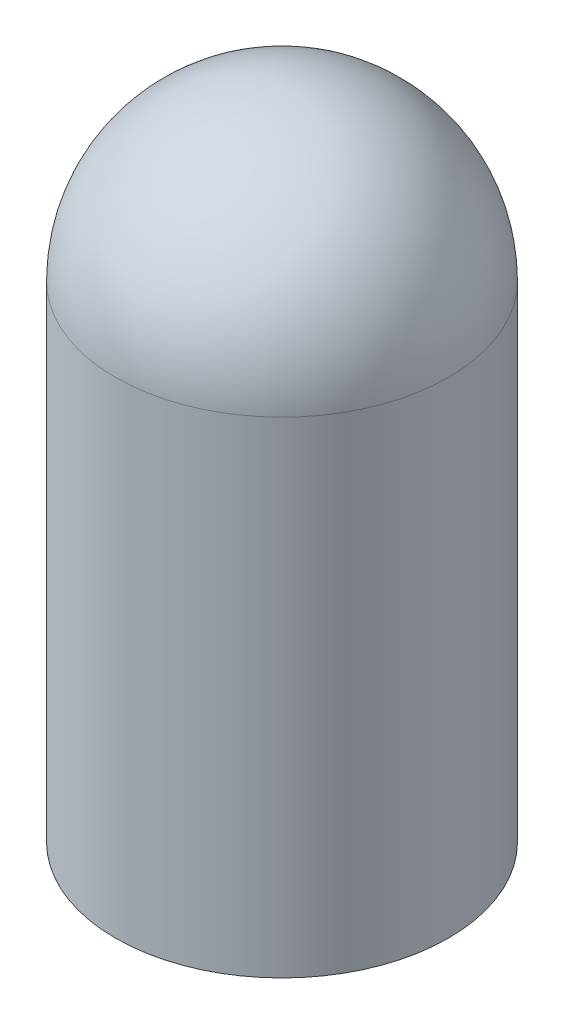
SolidWorks part; units mm, degrees
ref_plane "Front Plane" through (0, 0, 0) normal (0, 0, 1) x (1, 0, 0)
ref_plane "Top Plane" through (0, 0, 0) normal (0, 1, 0) x (1, 0, 0)
ref_plane "Right Plane" through (0, 0, 0) normal (1, 0, 0) x (0, 0, -1)
sketch "Sketch1" plane through (0, 0, 0) normal (0, 0, 1) x (1, 0, 0)
  line L0 (12, 0) -> (12, -35)
  line L1 (10.5, 0) -> (10.5, -35)
  line L2 (10.5, -35) -> (12, -35)
  line L3 (0, 12) -> (0, 10.5)
  line L4 (0, 12) -> (0, -44.4762) construction
  arc A0 (12, 0) -> (0, 12) centre (0, 0) ccw
  arc A1 (10.5, 0) -> (0, 10.5) centre (0, 0) ccw
  dimension "D1" = 21
  dimension "D2" = 24
  dimension "D3" = 35
revolve "Revolve1" add sketch "Sketch1" angle 360 about L4
